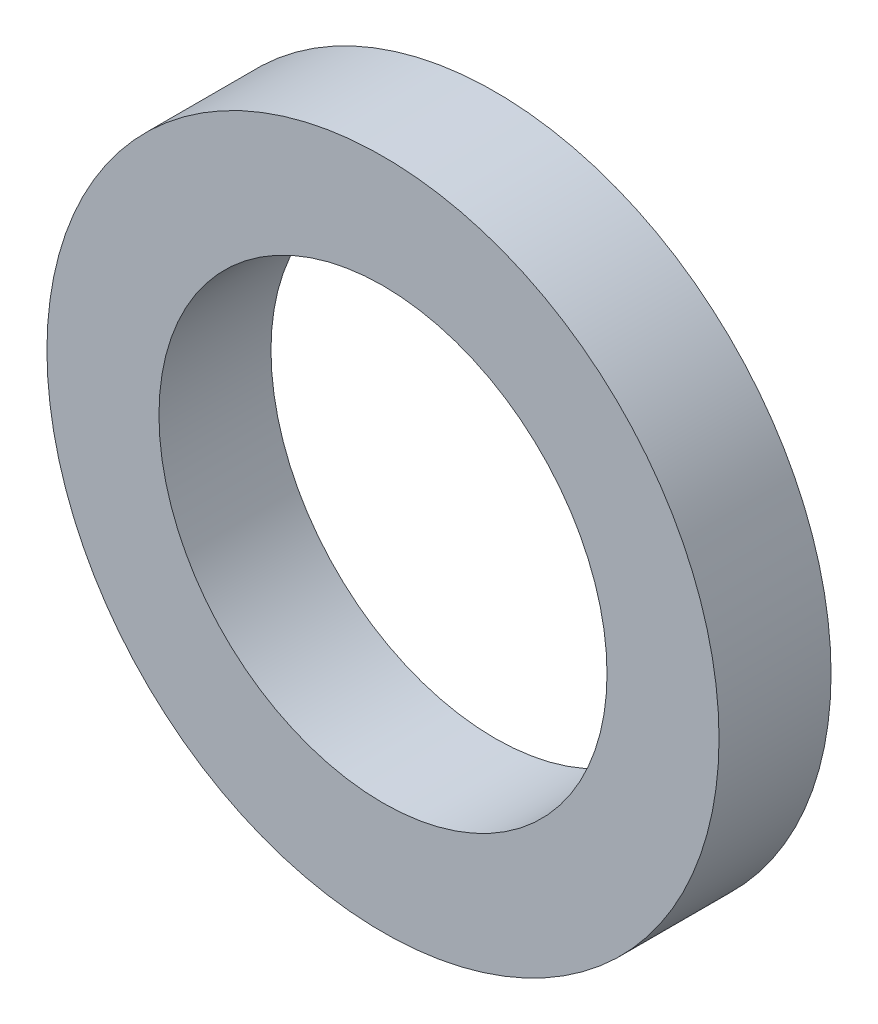
SolidWorks part; units mm, degrees
ref_plane "Front Plane" through (0, 0, 0) normal (0, 0, 1) x (1, 0, 0)
ref_plane "Top Plane" through (0, 0, 0) normal (0, 1, 0) x (1, 0, 0)
ref_plane "Right Plane" through (0, 0, 0) normal (1, 0, 0) x (0, 0, -1)
sketch "Sketch1" plane through (0, 0, 0) normal (0, 0, 1) x (1, 0, 0)
  circle A0 centre (0, 0) radius 15
  circle A1 centre (0, 0) radius 10
  dimension "D1" = 30
  dimension "D2" = 20
extrude "Boss-Extrude1" add sketch "Sketch1" along normal blind 5
